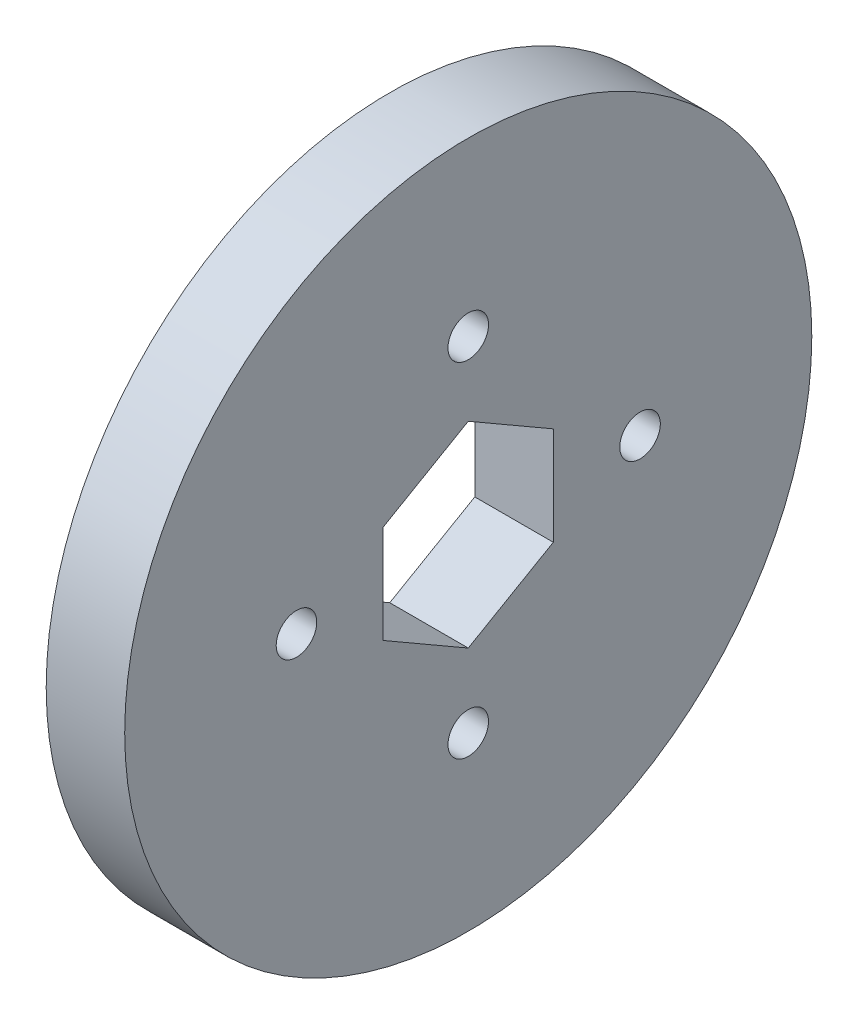
SolidWorks part; units mm, degrees
ref_plane "Plan de face" through (0, 0, 0) normal (0, 0, 1) x (1, 0, 0)
ref_plane "Plan de dessus" through (0, 0, 0) normal (0, 1, 0) x (1, 0, 0)
ref_plane "Plan de droite" through (0, 0, 0) normal (1, 0, 0) x (0, 0, -1)
sketch "Esquisse1" plane through (0, 0, 0) normal (-1, 0, 0) x (0, 0, 1)
  line L0 (16.0978, -71.6747) -> (16.0978, -45.4172) construction
  line L1 (16.0978, -51.0404) -> (9.5978, -54.7932)
  line L2 (9.5978, -54.7932) -> (9.5978, -62.2987)
  line L3 (9.5978, -62.2987) -> (16.0978, -66.0515)
  line L4 (16.0978, -66.0515) -> (22.5978, -62.2987)
  line L5 (22.5978, -62.2987) -> (22.5978, -54.7932)
  line L6 (22.5978, -54.7932) -> (16.0978, -51.0404)
  line L7 (29.2265, -58.546) -> (2.969, -58.546) construction
  circle A0 centre (16.0978, -58.546) radius 26.2575
  circle A1 centre (29.2265, -58.546) radius 1.55
  circle A2 centre (16.0978, -45.4172) radius 1.55
  circle A3 centre (2.969, -58.546) radius 1.55
  circle A4 centre (16.0978, -71.6747) radius 1.55
  circle A5 centre (16.0978, -58.546) radius 6.5 construction
  dimension "D1" = 13
  dimension "D2" = 26.2575
  dimension "D3" = 26.2575
extrude "Boss.-Extru.1" add sketch "Esquisse1" along normal blind 6
